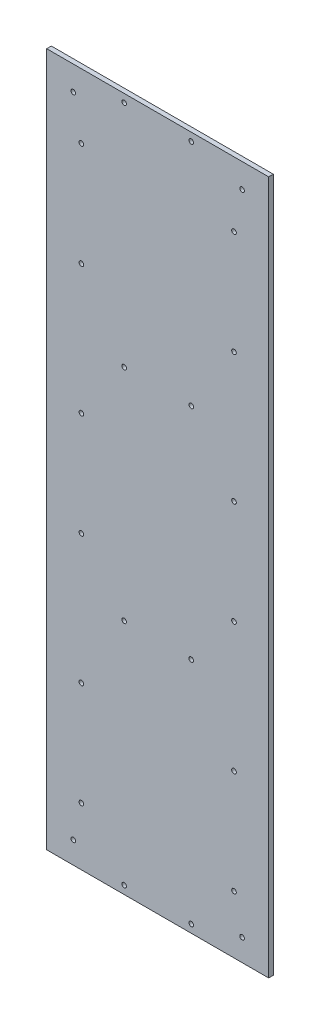
SolidWorks part; units mm, degrees
material "Alumina"
ref_plane "Front Plane" through (0, 0, 0) normal (0, 0, 1) x (1, 0, 0)
ref_plane "Top Plane" through (0, 0, 0) normal (0, 1, 0) x (1, 0, 0)
ref_plane "Right Plane" through (0, 0, 0) normal (1, 0, 0) x (0, 0, -1)
sketch "Sketch1" plane through (0, 0, 0) normal (0, 0, 1) x (1, 0, 0)
  line L1 (48, -150) -> (-48, -150)
  line L2 (48, -150) -> (48, 150)
  line L3 (48, 150) -> (-48, 150)
  line L4 (-48, -150) -> (-48, 150)
  line L5 (48, -150) -> (-48, 150) construction
  line L6 (48, 150) -> (-48, -150) construction
  point P0 (0, 0)
  dimension "D1" = 96
  dimension "D2" = 300
extrude "Boss-Extrude1" add sketch "Sketch1" along normal blind 2
sketch "Sketch2" plane through (0, 0, 2) normal (0, 0, 1) x (1, 0, 0)
  line L0 (-48, 150) -> (-48, -150) construction
  line L1 (48, 150) -> (-48, 150) construction
  line L2 (-48, -150) -> (48, -150) construction
  line L3 (48, -150) -> (48, 150) construction
  line L4 (0, -1.1) -> (0, 1.1) construction
  line L5 (-33, 77) -> (-33, -125) construction
  line L6 (33, 77) -> (33, -125) construction
  line L7 (-14.5, 146.5) -> (14.5, 146.5) construction
  line L8 (14.5, 146.5) -> (14.5, -146.5) construction
  line L9 (14.5, -146.5) -> (-14.5, -146.5) construction
  line L10 (-14.5, -146.5) -> (-14.5, 146.5) construction
  circle A0 centre (-33, 122) radius 1
  circle A1 centre (-33, 77) radius 1
  circle A9 centre (-33, -125) radius 1
  circle A13 centre (14.5, -146.5) radius 1
  circle A14 centre (-14.5, -146.5) radius 1
  circle A15 centre (-14.5, -47.5) radius 1
  circle A17 centre (-14.5, 47.5) radius 1
  circle A19 centre (-14.5, 146.5) radius 1
  circle A20 centre (14.5, 146.5) radius 1
  circle A21 centre (-33, -80) radius 1
  circle A22 centre (-33, -24) radius 1
  circle A23 centre (-33, 21) radius 1
  circle A24 centre (33, 21) radius 1
  circle A25 centre (33, -24) radius 1
  circle A26 centre (33, -80) radius 1
  circle A27 centre (33, -125) radius 1
  circle A28 centre (33, 77) radius 1
  circle A29 centre (33, 122) radius 1
  circle A30 centre (14.5, -47.5) radius 1
  circle A31 centre (14.5, 47.5) radius 1
  dimension "D1" = 2
  dimension "D3" = 28
  dimension "D4" = 2
  dimension "D6" = 15
  dimension "D10" = 2
  dimension "D11" = 33.5
  dimension "D13" = 3.5
  dimension "D15" = 2
  dimension "D8" = 2
  dimension "D14" = 2
  dimension "D17" = 45
  dimension "D18" = 56
  dimension "D19" = 2
  dimension "D20" = 45
  dimension "D12" = 2
  dimension "D21" = 2
  dimension "D23" = 2
  dimension "D24" = 99
  dimension "D25" = 2
  dimension "D2" = 15
  dimension "D5" = 45
  dimension "D9" = 25
  dimension "D16" = 3.5
  dimension "D7" = 15
  dimension "D22" = 99
extrude "Cut-Extrude1" cut sketch "Sketch2" against normal blind 10
sketch "Sketch3" plane through (0, 0, 2) normal (0, 0, 1) x (1, 0, 0)
  line L0 (-36.5, 139.5) -> (36.5, 139.5) construction
  line L1 (36.5, 139.5) -> (36.5, -140.5) construction
  line L2 (36.5, -140.5) -> (-36.5, -140.5) construction
  line L3 (-36.5, -140.5) -> (-36.5, 139.5) construction
  line L4 (-48, 150) -> (-48, -150) construction
  line L5 (48, -150) -> (48, 150) construction
  line L6 (48, 150) -> (-48, 150) construction
  line L7 (-48, -150) -> (48, -150) construction
  circle A0 centre (-36.5, 139.5) radius 1
  circle A1 centre (36.5, 139.5) radius 1
  circle A2 centre (-36.5, -140.5) radius 1
  circle A3 centre (36.5, -140.5) radius 1
  dimension "D5" = 2
  dimension "D6" = 2
  dimension "D7" = 2
  dimension "D8" = 2
  dimension "D1" = 11.5
  dimension "D2" = 11.5
  dimension "D3" = 10.5
  dimension "D4" = 9.5
extrude "Cut-Extrude2" cut sketch "Sketch3" against normal blind 10
